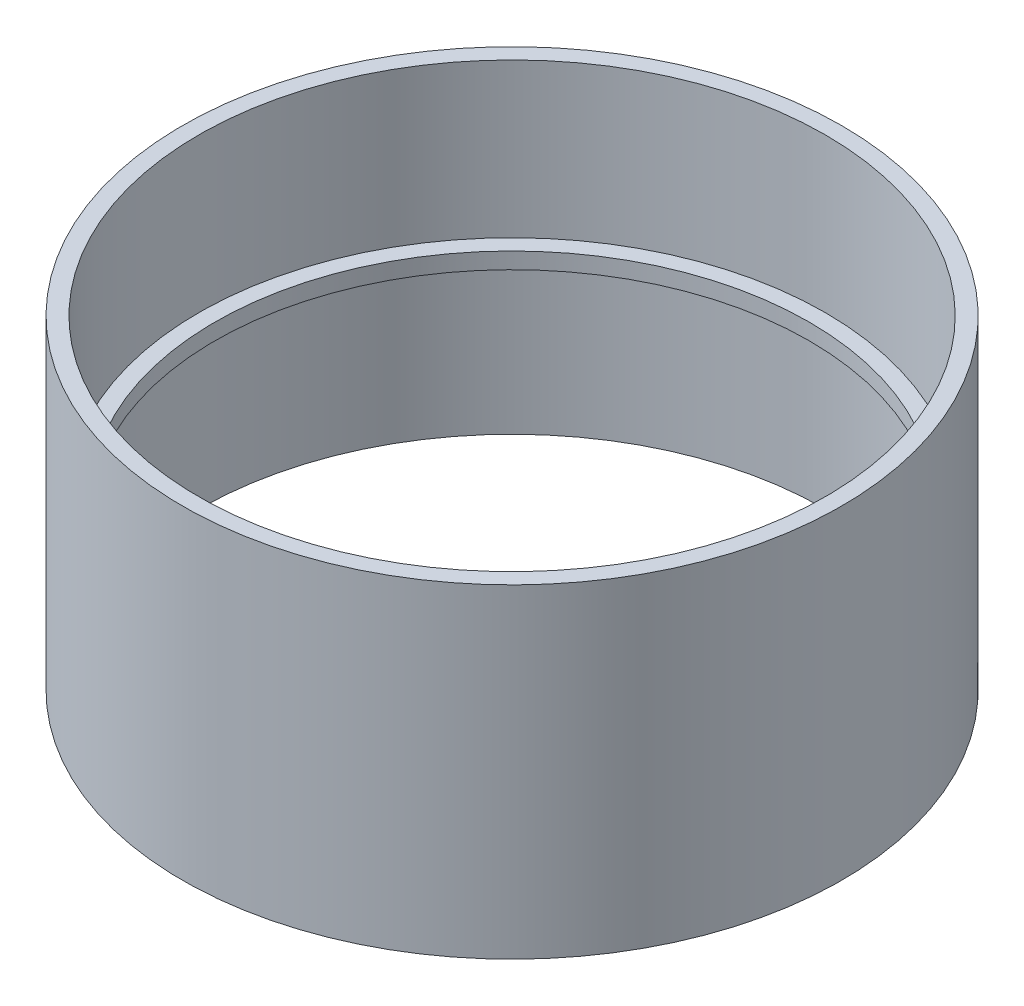
SolidWorks part; units mm, degrees
ref_plane "Front Plane" through (0, 0, 0) normal (0, 0, 1) x (1, 0, 0)
ref_plane "Top Plane" through (0, 0, 0) normal (0, 1, 0) x (1, 0, 0)
ref_plane "Right Plane" through (0, 0, 0) normal (1, 0, 0) x (0, 0, -1)
sketch "Sketch1" plane through (0, 0, 0) normal (0, 0, 1) x (1, 0, 0)
  line L0 (0, 0) -> (0, 17.5945) construction
  line L2 (29, 0) -> (30.5, 0)
  line L3 (29, 0) -> (29, 30)
  line L4 (29, 30) -> (30.5, 30)
  line L5 (30.5, 0) -> (30.5, 30)
  line L6 (29, 15.75) -> (27.5, 15.75)
  line L7 (29, 15.75) -> (29, 14.25)
  line L8 (29, 14.25) -> (27.5, 14.25)
  line L9 (27.5, 15.75) -> (27.5, 14.25)
  dimension "D1" = 30
  dimension "D2" = 1.5
  dimension "D3" = 1.5
  dimension "D4" = 1.5
  dimension "D5" = 29
  dimension "D6" = 14.25
revolve "Revolve1" add sketch "Sketch1" angle 360 about L0
